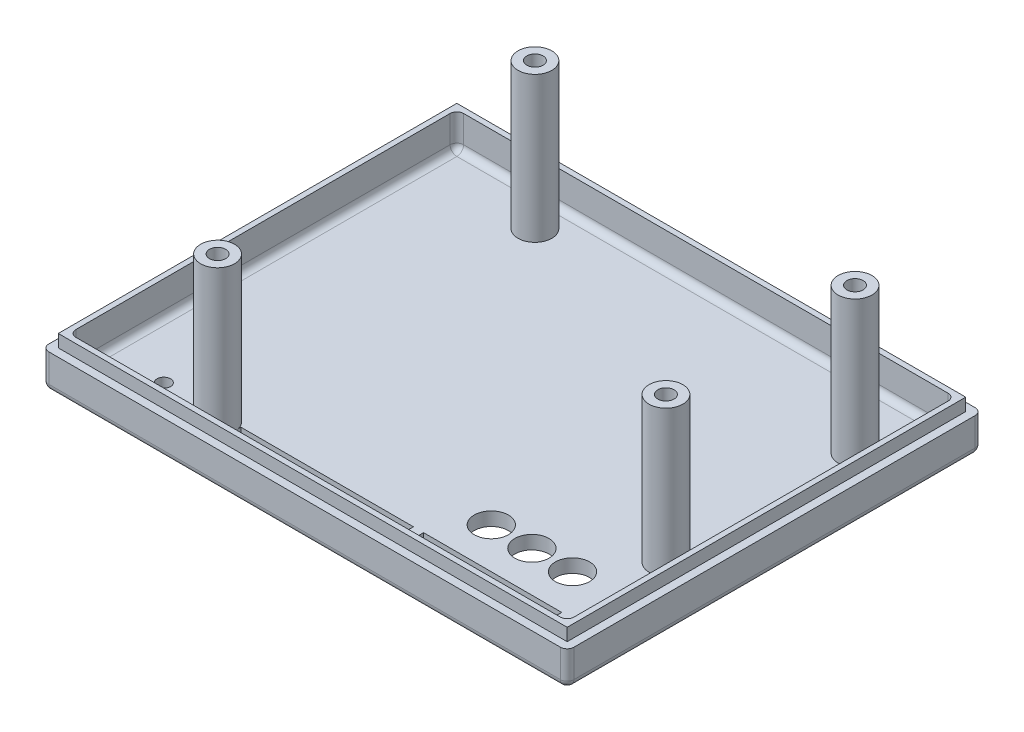
SolidWorks part; units mm, degrees
ref_plane "Front" through (0, 0, 0) normal (0, 0, 1) x (1, 0, 0)
ref_plane "Top" through (0, 0, 0) normal (0, 1, 0) x (1, 0, 0)
ref_plane "Right" through (0, 0, 0) normal (1, 0, 0) x (0, 0, -1)
sketch "Sketch1" plane through (0, 0, 0) normal (0, 1, 0) x (1, 0, 0)
  line L0 (-38.8, 30.65) -> (38.8, -30.65) construction
  line L1 (-38.8, 30.65) -> (38.8, 30.65)
  line L2 (-38.8, 30.65) -> (-38.8, -30.65)
  line L3 (-38.8, -30.65) -> (38.8, -30.65)
  line L4 (38.8, 30.65) -> (38.8, -30.65)
  line L5 (38.8, 30.65) -> (-38.8, -30.65) construction
  point P0 (0, 0)
  dimension "D1" = 61.3
  dimension "D2" = 77.6
extrude "Boss-Extrude1" add sketch "Sketch1" along normal blind 7
sketch "Sketch2" plane through (0, 7, 0) normal (0, 1, 0) x (1, 0, 0)
  line L0 (38.8, 30.65) -> (-38.8, 30.65) construction
  line L1 (-37.6, 29.45) -> (37.6, 29.45)
  line L2 (-37.6, 29.45) -> (-37.6, -29.45)
  line L3 (-37.6, -29.45) -> (37.6, -29.45)
  line L4 (37.6, 29.45) -> (37.6, -29.45)
  line L5 (-38.8, 30.65) -> (-38.8, -30.65) construction
  line L6 (-38.8, -30.65) -> (38.8, -30.65) construction
  line L7 (38.8, -30.65) -> (38.8, 30.65) construction
  dimension "D1" = 1.2
  dimension "D2" = 1.2
  dimension "D3" = 1.2
  dimension "D4" = 1.2
extrude "Cut-Extrude-Thin1" cut sketch "Sketch2" against normal blind 1.85 thin thin type one direction wall 10
sketch "Sketch3" plane through (0, 7, 0) normal (0, 1, 0) x (1, 0, 0)
  line L0 (36.8, 28.65) -> (-36.8, -28.65) construction
  line L1 (-36.8, 28.65) -> (36.8, 28.65)
  line L2 (-36.8, 28.65) -> (-36.8, -28.65)
  line L3 (-36.8, -28.65) -> (36.8, -28.65)
  line L4 (36.8, 28.65) -> (36.8, -28.65)
  line L5 (-36.8, 28.65) -> (36.8, -28.65) construction
  point P0 (0, 0)
  dimension "D1" = 73.6
  dimension "D2" = 57.3
extrude "Cut-Extrude1" cut sketch "Sketch3" against normal blind 5
fillet "Fillet1" radius 1 16 edges at (0, 0, -30.65) (-38.8, 0, 0) (0, 0, 30.65) (38.8, 0, 0) (0, 2, 28.65) (-36.8, 2, 0) (0, 2, -28.65) (36.8, 2, 0) (-38.8, 2.575, 30.65) (38.8, 2.575, 30.65) (38.8, 2.575, -30.65) (-38.8, 2.575, -30.65) (36.8, 4.5, 28.65) (36.8, 4.5, -28.65) (-36.8, 4.5, -28.65) (-36.8, 4.5, 28.65)
sketch "Sketch5" plane through (0, 2, 0) normal (0, 1, 0) x (1, 0, 0)
  line L1 (30.3, -22.95) -> (9.89, -22.95)
  line L2 (30.3, -22.95) -> (30.3, -25.65)
  line L3 (30.3, -25.65) -> (9.89, -25.65)
  line L4 (9.89, -22.95) -> (9.89, -25.65)
  line L13 (-35.8, -28.65) -> (35.8, -28.65) construction
  line L14 (8.39, -22.95) -> (-17.1, -22.95)
  line L15 (8.39, -22.95) -> (8.39, -25.65)
  line L16 (8.39, -25.65) -> (-17.1, -25.65)
  line L17 (-17.1, -22.95) -> (-17.1, -25.65)
  dimension "D1" = 2.7
  dimension "D4" = 2.7
  dimension "D5" = 5.7
  dimension "D9" = 1.5
  dimension "D11" = 20.41
  dimension "D12" = 47.4
extrude "Cut-Extrude3" cut sketch "Sketch5" against normal up to next
sketch "Sketch6" plane through (0, 2, 0) normal (0, 1, 0) x (1, 0, 0)
  line L7 (36.8, -27.65) -> (36.8, 27.65) construction
  line L9 (35.8, 28.65) -> (-35.8, 28.65) construction
  circle A4 centre (31.6, 19.09) radius 2.5
  circle A5 centre (31.6, -8.85) radius 2.5
  circle A6 centre (-19.5, -24.01) radius 2.5
  circle A7 centre (-20.8, 24.19) radius 2.5
  dimension "D19" = 5
  dimension "D20" = 5
  dimension "D21" = 5
  dimension "D22" = 5
  dimension "D14" = 27.94
  dimension "D15" = 5.2
  dimension "D17" = 52.4
  dimension "D18" = 48.2
  dimension "D16" = 9.56
  dimension "D23" = 5.1
  dimension "D5" = 51.1
extrude "Boss-Extrude2" add sketch "Sketch6" along normal blind 21.5
sketch "Sketch7" plane through (0, 23.5, 0) normal (0, 1, 0) x (1, 0, 0)
  circle A0 centre (31.6, 19.09) radius 1.2
  circle A1 centre (31.6, -8.85) radius 1.2
  circle A2 centre (-20.8, 24.19) radius 1.2
  circle A3 centre (-19.5, -24.01) radius 1.2
  dimension "D1" = 2.4
  dimension "D2" = 2.4
  dimension "D3" = 2.4
  dimension "D4" = 2.4
extrude "Cut-Extrude4" cut sketch "Sketch7" against normal blind 5
sketch "Sketch8" plane through (0, 2, 0) normal (0, 1, 0) x (1, 0, 0)
  line L1 (8.39, -22.95) -> (-17.1, -22.95) construction
  circle A0 centre (-28.5, -22.95) radius 1
  circle A1 centre (-19.5, -24.01) radius 2.5 construction
  dimension "D1" = 2
  dimension "D2" = 9
extrude "Cut-Extrude5" cut sketch "Sketch8" against normal up to next
sketch "Sketch10" plane through (0, 0, 0) normal (0, -1, 0) x (1, 0, 0)
  line L0 (9.89, 22.95) -> (9.89, 16.95) construction
  line L1 (9.89, 16.95) -> (29.89, 16.95) construction
  circle A0 centre (13.89, 16.95) radius 2.525
  circle A1 centre (19.89, 16.95) radius 2.525
  circle A2 centre (25.89, 16.95) radius 2.525
  dimension "D2" = 5.05
  dimension "D3" = 5.05
  dimension "D4" = 5.05
  dimension "D1" = 6
  dimension "D5" = 4
  dimension "D6" = 10
  dimension "D7" = 16
extrude "Cut-Extrude6" cut sketch "Sketch10" against normal blind 2
equation "\"D2@Sketch2\"=\"D1@Sketch2\""
equation "\"D3@Sketch2\"=\"D1@Sketch2\""
equation "\"D4@Sketch2\"=\"D1@Sketch2\""
equation "\"D4@Sketch5\"=\"D1@Sketch5\""
equation "\"D20@Sketch6\"=\"D19@Sketch6\""
equation "\"D21@Sketch6\"=\"D19@Sketch6\""
equation "\"D22@Sketch6\"=\"D20@Sketch6\""
equation "\"D2@Sketch7\"=\"D1@Sketch7\""
equation "\"D4@Sketch7\"=\"D1@Sketch7\""
